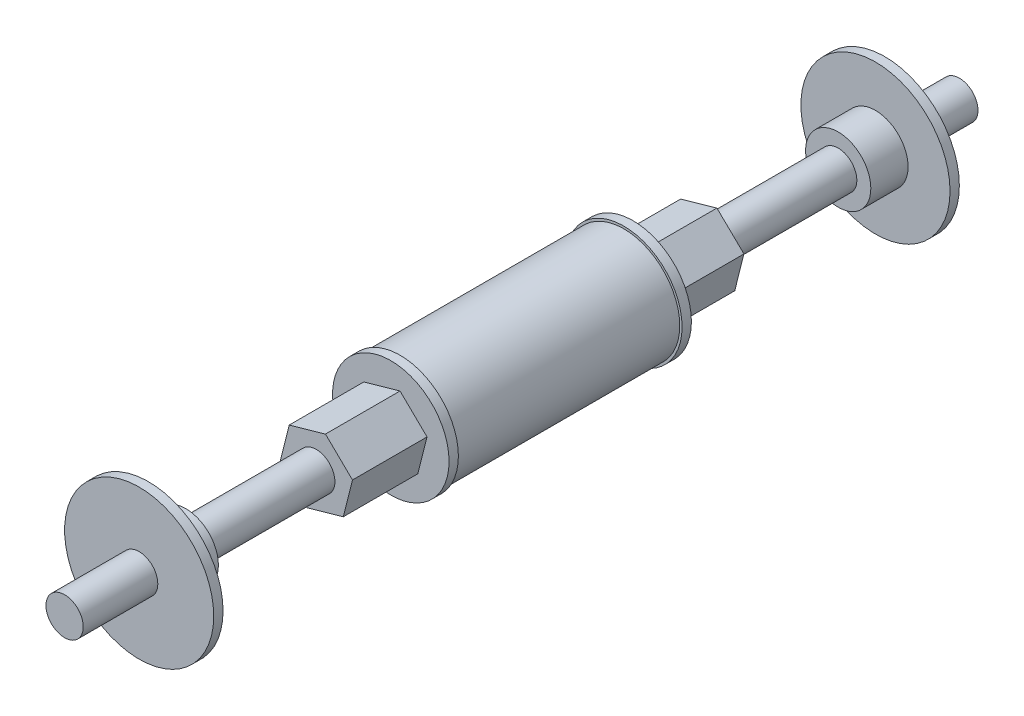
SolidWorks part; units mm, degrees
ref_plane "Front Plane" through (0, 0, 0) normal (0, 0, 1) x (1, 0, 0)
ref_plane "Top Plane" through (0, 0, 0) normal (0, 1, 0) x (1, 0, 0)
ref_plane "Right Plane" through (0, 0, 0) normal (1, 0, 0) x (0, 0, -1)
sketch "Sketch1" plane through (0, 0, 0) normal (0, 0, 1) x (1, 0, 0)
  circle A0 centre (0, 0) radius 9.525
  point P3 (0, 0)
  dimension "D1" = 19.05
extrude "Boss-Extrude1" add sketch "Sketch1" along normal blind 19.05
sketch "Sketch2" plane through (0, 0, 19.05) normal (0, 0, 1) x (1, 0, 0)
  circle A0 centre (0, 0) radius 9.9219
  dimension "D1" = 19.8438
extrude "Boss-Extrude2" add sketch "Sketch2" along normal blind 1.5875 contours A0
sketch "Sketch3" plane through (0, 0, 20.6375) normal (0, 0, 1) x (1, 0, 0)
  line L1 (4.6031, -4.4692) -> (6.172, 1.7518)
  line L2 (6.172, 1.7518) -> (1.5689, 6.221)
  line L3 (1.5689, 6.221) -> (-4.6031, 4.4692)
  line L4 (-4.6031, 4.4692) -> (-6.172, -1.7518)
  line L5 (-6.172, -1.7518) -> (-1.5689, -6.221)
  line L6 (-1.5689, -6.221) -> (4.6031, -4.4692)
  circle A0 centre (0, 0) radius 5.5562 construction
  dimension "D1" = 5.5562
extrude "Boss-Extrude3" add sketch "Sketch3" along normal blind 12.7
sketch "Sketch4" plane through (0, 0, 33.3375) normal (0, 0, 1) x (1, 0, 0)
  circle A0 centre (0, 0) radius 3.175
  dimension "D1" = 6.35
extrude "Boss-Extrude4" add sketch "Sketch4" along normal blind 22.225
sketch "Sketch5" plane through (0, 0, 55.5625) normal (0, 0, 1) x (1, 0, 0)
  circle A0 centre (0, 0) radius 5.5562
  dimension "D1" = 11.1125
extrude "Boss-Extrude6" add sketch "Sketch5" along normal blind 6.35
sketch "Sketch6" plane through (0, 0, 61.9125) normal (0, 0, 1) x (1, 0, 0)
  circle A0 centre (0, 0) radius 12.7
  dimension "D1" = 25.4
extrude "Boss-Extrude7" add sketch "Sketch6" along normal blind 1.5875
sketch "Sketch7" plane through (0, 0, 63.5) normal (0, 0, 1) x (1, 0, 0)
  circle A0 centre (0, 0) radius 3.175
  dimension "D1" = 6.35
extrude "Boss-Extrude8" add sketch "Sketch7" along normal blind 12.7
mirror "Mirror1" about plane through (0, 0, 0) normal (0, 0, 1) of "Boss-Extrude8", "Boss-Extrude7", "Boss-Extrude4", "Boss-Extrude6", "Boss-Extrude3", "Boss-Extrude2", "Boss-Extrude1"
